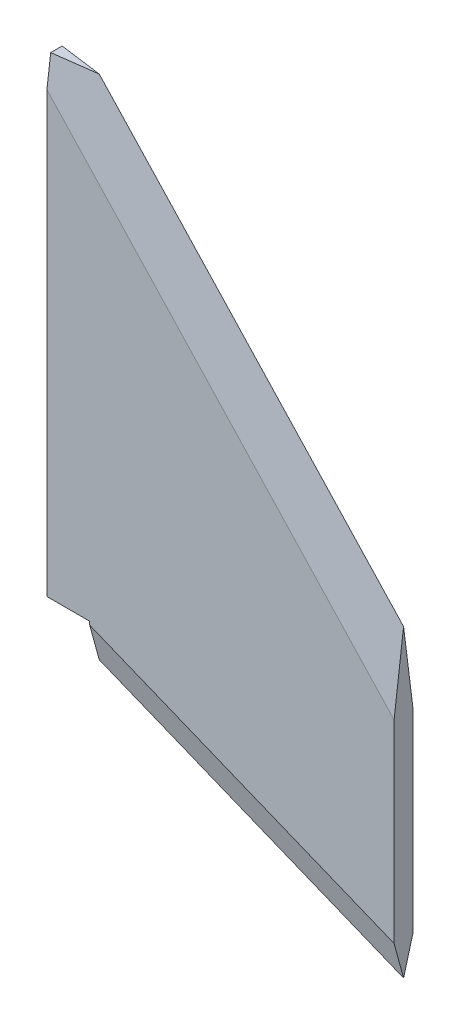
SolidWorks part; units mm, degrees
ref_plane "Front Plane" through (0, 0, 0) normal (0, 0, 1) x (1, 0, 0)
ref_plane "Top Plane" through (0, 0, 0) normal (0, 1, 0) x (1, 0, 0)
ref_plane "Right Plane" through (0, 0, 0) normal (1, 0, 0) x (0, 0, -1)
sketch "Sketch2" plane through (0, 0, 0) normal (0, 0, 1) x (1, 0, 0)
  line L0 (0, 0) -> (0, 127)
  line L1 (0, 127) -> (76.2, 45.2882)
  line L2 (76.2, 45.2882) -> (76.2, -30.9118)
  line L3 (76.2, -30.9118) -> (0, 0)
  line L9 (0, 127) -> (-10.7188, 127)
  line L10 (0, 127) -> (0, 9.525)
  line L11 (0, 9.525) -> (-10.7188, 9.525)
  line L12 (-10.7188, 127) -> (-10.7188, 9.525)
  dimension "D1" = 127
  dimension "D2" = 76.2
  dimension "D3" = 76.2
  dimension "D4" = 81.7118
  dimension "D5" = 10.7188
  dimension "D6" = 117.475
extrude "Boss-Extrude3" add sketch "Sketch2" along normal blind 4.7498 contours L3 L2 L1 L0 | L10 L9 L12 L11
ref_plane "Plane3" through (12.8545, -13.7843, 0) normal (0.682, -0.7313, 0) x (0, 0, -1)
ref_plane "Plane4" through (0, 0, 0) normal (-0.9267, 0.3759, 0) x (0, 0, -1)
sketch "Sketch8" plane through (0, 0, 0) normal (-0.9267, 0.3759, 0) x (0, 0, -1)
  line L0 (-2.3749, 0) -> (0, -8.0385)
  line L1 (-4.7498, 0) -> (0, 0) construction
  line L2 (-2.3749, 0) -> (-4.7498, -8.0385)
  line L3 (-4.7498, -8.0385) -> (-5.3143, -8.0385)
  line L4 (-5.3143, -8.0385) -> (-5.3143, 2.3102)
  line L5 (-5.3143, 2.3102) -> (0.7503, 2.3102)
  line L6 (0.7503, 2.3102) -> (0.7503, -8.0385)
  line L7 (0.7503, -8.0385) -> (0, -8.0385)
  dimension "D1" = 4.7498
  dimension "D2" = 8.382
  dimension "D3" = 32.918
extrude "Cut-Extrude17" cut sketch "Sketch8" against normal blind 101.6 and the other way blind 5.08 contours L4 L5 L6 L7 L0 L2 L3
sketch "Sketch9" plane through (12.8545, -13.7843, 0) normal (0.682, -0.7313, 0) x (0, 0, -1)
  line L0 (-2.3749, 86.6153) -> (0, 73.6226)
  line L1 (-4.7498, 86.6153) -> (0, 86.6153) construction
  line L2 (0, 86.6153) -> (0, 40.5624) construction
  line L3 (-2.3749, 86.6153) -> (-4.7498, 73.6226)
  line L4 (-4.7498, 86.6153) -> (-4.7498, 40.5624) construction
  line L5 (-4.7498, 73.6226) -> (-6.5312, 73.6226)
  line L6 (-6.5312, 73.6226) -> (-6.5312, 91.3015)
  line L7 (-6.5312, 91.3015) -> (0.8726, 91.3015)
  line L8 (0.8726, 91.3015) -> (0.8726, 73.6226)
  line L9 (0.8726, 73.6226) -> (0, 73.6226)
  dimension "D1" = 13.208
  dimension "D2" = 4.7498
  dimension "D3" = 20.717
extrude "Cut-Extrude18" cut sketch "Sketch9" against normal blind 127 and the other way blind 101.6
